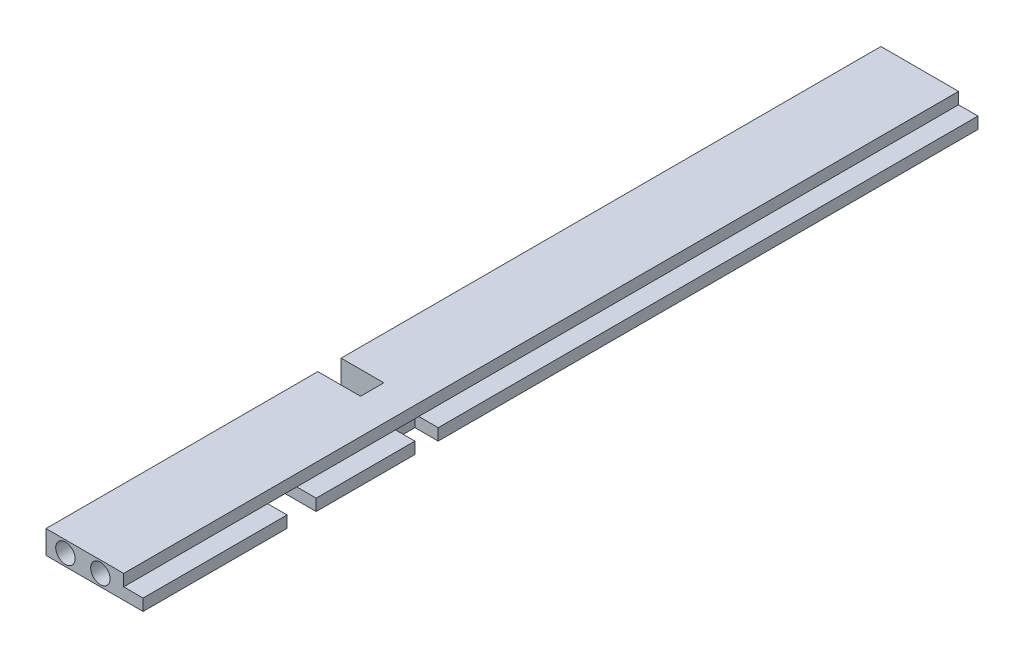
SolidWorks part; units mm, degrees
material "Plywood"
ref_plane "Plan de face" through (0, 0, 0) normal (0, 0, 1) x (1, 0, 0)
ref_plane "Plan de dessus" through (0, 0, 0) normal (0, 1, 0) x (1, 0, 0)
ref_plane "Plan de droite" through (0, 0, 0) normal (1, 0, 0) x (0, 0, -1)
sketch "Esquisse1" plane through (0, 0, 0) normal (0, 0, 1) x (1, 0, 0)
  line L0 (0, 0) -> (0, 6)
  line L1 (0, 6) -> (20, 6)
  line L2 (20, 6) -> (20, 3)
  line L3 (20, 3) -> (25, 3)
  line L4 (25, 3) -> (25, 0)
  line L5 (25, 0) -> (0, 0)
  dimension "D1" = 6
  dimension "D2" = 3
  dimension "D3" = 5
  dimension "D4" = 25
extrude "Boss.-Extru.1" add sketch "Esquisse1" along normal blind 215
sketch "Esquisse3" plane through (0, 0, 0) normal (0, -1, 0) x (1, 0, 0)
  line L0 (25, 215) -> (25, 0) construction
  line L1 (25, 170.4246) -> (17, 170.4246)
  line L2 (25, 170.4246) -> (25, 177.9246)
  line L3 (25, 177.9246) -> (17, 177.9246)
  line L4 (17, 170.4246) -> (17, 177.9246)
  line L5 (0, 215) -> (0, 0) construction
  line L6 (0, 170.4246) -> (11, 170.4246)
  line L7 (0, 170.4246) -> (0, 177.9246)
  line L8 (0, 177.9246) -> (11, 177.9246)
  line L9 (11, 170.4246) -> (11, 177.9246)
  line L10 (0, 177.9246) -> (11, 177.9246) construction
  line L11 (0, 170.4246) -> (11, 170.4246) construction
  line L12 (11, 177.9246) -> (11, 170.4246) construction
  line L13 (17, 177.9246) -> (17, 170.4246) construction
extrude "Enlèv. mat.-Extru.1" cut sketch "Esquisse3" against normal blind 3
sketch "Esquisse4" plane through (0, 0, 0) normal (0, -1, 0) x (1, 0, 0)
  line L0 (0, 170.4246) -> (0, 0) construction
  line L1 (0, 139) -> (11, 139)
  line L2 (0, 139) -> (0, 145)
  line L3 (0, 145) -> (11, 145)
  line L4 (11, 139) -> (11, 145)
  line L5 (1, 139) -> (11, 139) construction
  line L6 (1, 145) -> (11, 145) construction
  line L7 (11, 145) -> (11, 139) construction
extrude "Enlèv. mat.-Extru.2" cut sketch "Esquisse4" against normal through all
sketch "Esquisse5" plane through (0, 0, 0) normal (0, -1, 0) x (1, 0, 0)
  line L0 (25, 170.4246) -> (25, 0) construction
  line L1 (25, 139) -> (19, 139)
  line L2 (25, 139) -> (25, 145)
  line L3 (25, 145) -> (19, 145)
  line L4 (19, 139) -> (19, 145)
  line L5 (25, 139) -> (19, 139) construction
  line L6 (19, 145) -> (25, 145) construction
  line L7 (19, 145) -> (19, 139) construction
extrude "Enlèv. mat.-Extru.3" cut sketch "Esquisse5" against normal blind 3
sketch "Esquisse8" plane through (0, 0, 215) normal (0, 0, 1) x (1, 0, 0)
  line L0 (0, 0) -> (25, 0) construction
  line L1 (0, 6) -> (0, 0) construction
  circle A0 centre (5, 3) radius 2.5
  dimension "D1" = 5
  dimension "D2" = 3
  dimension "D3" = 5
extrude "Enlèv. mat.-Extru.4" cut sketch "Esquisse8" against normal blind 10
pattern_linear "Répétition linéaire1" count 2 spacing 9 along (1, 0, 0) of "Enlèv. mat.-Extru.4"
